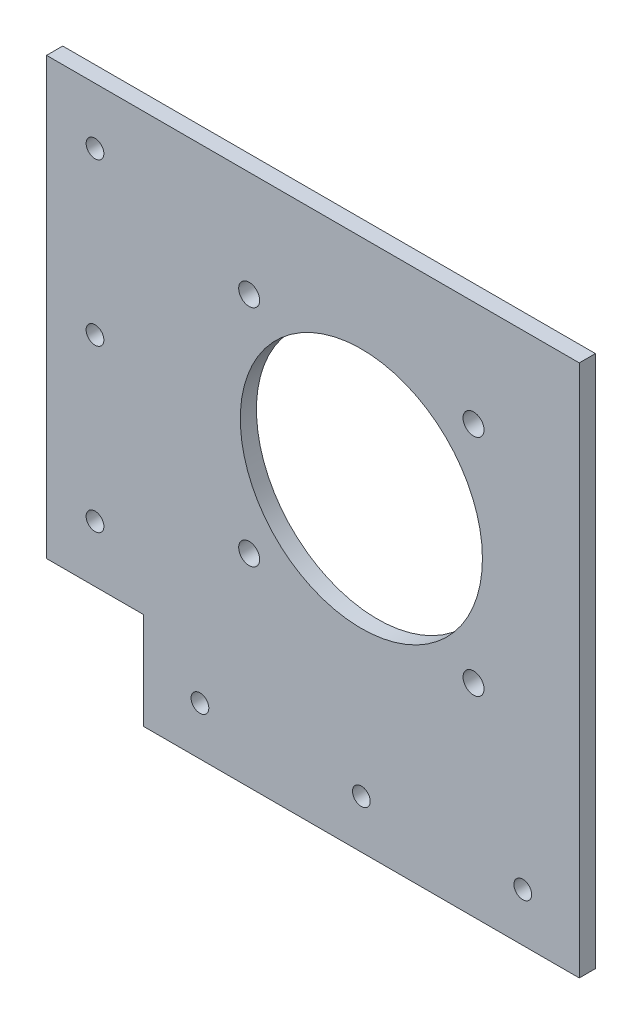
SolidWorks part; units mm, degrees
ref_plane "前视基准面" through (0, 0, 0) normal (0, 0, 1) x (1, 0, 0)
ref_plane "上视基准面" through (0, 0, 0) normal (0, 1, 0) x (1, 0, 0)
ref_plane "右视基准面" through (0, 0, 0) normal (1, 0, 0) x (0, 0, -1)
sketch "草图1" plane through (0, 0, 0) normal (0, 0, 1) x (1, 0, 0)
  line L0 (-150, 165) -> (-150, 0) construction
  line L1 (0, 0) -> (-135, 0)
  line L2 (0, 0) -> (0, 165)
  line L3 (0, 165) -> (-165, 165)
  line L4 (-165, 30) -> (-165, 165)
  line L5 (-165, 15) -> (0, 15) construction
  line L6 (-67.5, 165) -> (-67.5, 197.2983) construction
  line L9 (-165, 30) -> (-135, 30)
  line L10 (-135, 0) -> (-135, 30)
  line L12 (-67.5, 97.5) -> (0, 97.5) construction
  line L13 (-165, 97.5) -> (0, 97.5) construction
  line L14 (-32.75, 62.75) -> (-102.25, 62.75) construction
  line L15 (-32.75, 62.75) -> (-32.75, 132.25) construction
  line L16 (-32.75, 132.25) -> (-102.25, 132.25) construction
  line L17 (-102.25, 62.75) -> (-102.25, 132.25) construction
  line L18 (-32.75, 62.75) -> (-102.25, 132.25) construction
  line L19 (-32.75, 132.25) -> (-102.25, 62.75) construction
  line L20 (-67.5, 0) -> (-67.5, 165) construction
  circle A0 centre (-67.5, 97.5) radius 37.5
  circle A1 centre (-102.25, 132.25) radius 3.25
  circle A2 centre (-32.75, 132.25) radius 3.25
  circle A3 centre (-32.75, 62.75) radius 3.25
  circle A4 centre (-102.25, 62.75) radius 3.25
  circle A5 centre (-150, 147.5) radius 2.75
  circle A6 centre (-150, 97.5) radius 2.75
  circle A7 centre (-67.5, 15) radius 2.75
  circle A8 centre (-17.5, 15) radius 2.75
  circle A9 centre (-117.5, 15) radius 2.75
  circle A10 centre (-150, 47.5) radius 2.75
  point P3 (-67.5, 165)
  point P13 (-429.6887, 0)
  point P46 (-67.5, 97.5)
  dimension "D5" = 50
  dimension "D6" = 50
  dimension "D7" = 50
  dimension "D8" = 50
  dimension "D10" = 6.5
  dimension "D11" = 75
  dimension "D14" = 5.5
  dimension "D1" = 30
  dimension "D2" = 30
  dimension "D3" = 15
  dimension "D4" = 15
  dimension "D9" = 69.5
  dimension "D12" = 165
  dimension "D13" = 165
extrude "凸台-拉伸1" add sketch "草图1" along normal blind 5
